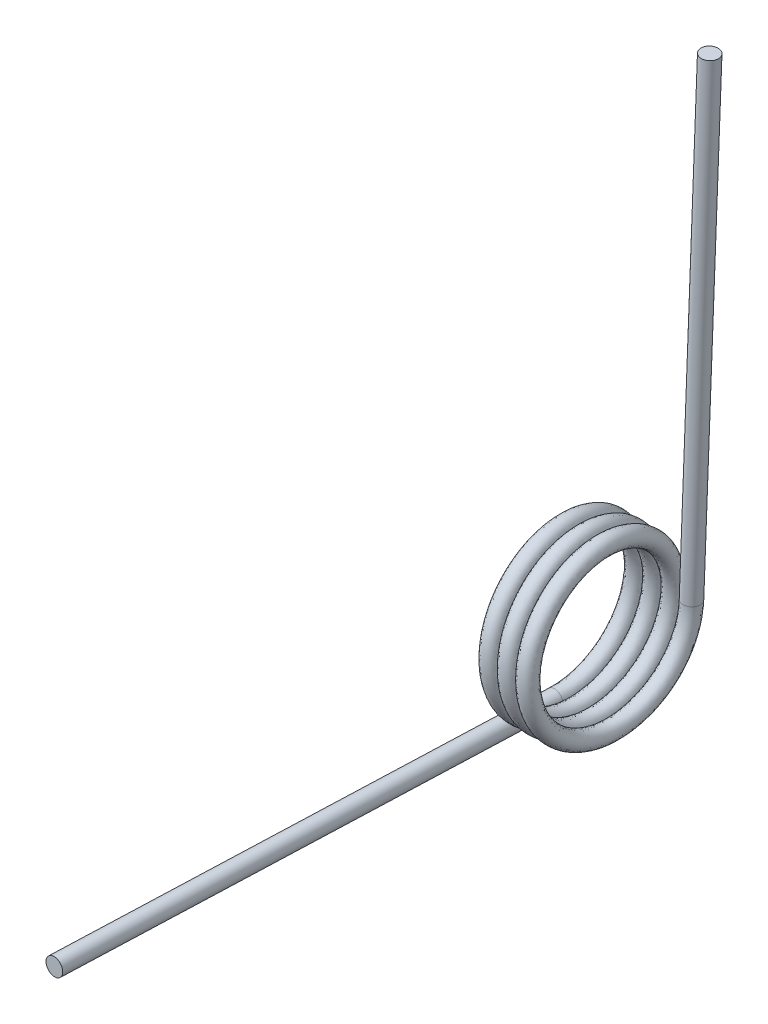
SolidWorks part; units mm, degrees
ref_plane "Front" through (0, 0, 0) normal (0, 0, 1) x (1, 0, 0)
ref_plane "Top" through (0, 0, 0) normal (0, 1, 0) x (1, 0, 0)
ref_plane "Right" through (0, 0, 0) normal (1, 0, 0) x (0, 0, -1)
sketch "Sketch1" plane through (0, 0, 0) normal (1, 0, 0) x (0, 0, -1)
  line L0 (0, 0) -> (0, -1.8034) construction
  line L1 (0, -1.8034) -> (0, -2.032) construction
  line L2 (0, -2.032) -> (0, -2.2606) construction
  circle A0 centre (0, 0) radius 1.8034 construction
  circle A1 centre (0, 0) radius 2.2606 construction
  circle A2 centre (0, 0) radius 2.032
  circle A3 centre (0, -2.032) radius 0.2286 construction
  circle A4 centre (0, 0) radius 1.3843 construction
curve "Helix/Spiral1" pitch 0.4826 height 1.5684 turns 3.25
ref_plane "Plane1" through (0, -2.032, 0) normal (0.0378, 0, -0.9993) x (0.9953, 0.0893, 0.0376)
sketch "Sketch2" plane through (0, -2.032, 0) normal (0.0378, 0, -0.9993) x (0.9953, 0.0893, 0.0376)
  circle A0 centre (0, 0) radius 0.2286
  dimension "D1" = 0.4572
sweep "Sweep1" add profiles "Sketch2" path "Helix/Spiral1"
sketch "Sketch3" plane through (0, 0, 0) normal (-0.0378, 0, 0.9993) x (-0.9953, -0.0893, -0.0376)
  circle A1 centre (0.1814, 2.0239) radius 0.2286
  circle A2 centre (0.1814, 2.0239) radius 0.2286
  dimension "D1" = 0
extrude "Extrude1" add sketch "Sketch3" along normal blind 12.7
sketch "Sketch4" plane through (0.0022, 0.0592, 0) normal (0.0378, 0.9993, 0) x (0.9953, -0.0376, -0.0893)
  circle A1 centre (1.7425, 1.884) radius 0.2286
  circle A2 centre (1.7425, 1.884) radius 0.2286
  dimension "D1" = 0
extrude "Extrude2" add sketch "Sketch4" along normal blind 12.7
sketch "Sketch5" plane through (0, 0, 0) normal (1, 0, 0) x (0, 0, -1)
  circle A0 centre (0, 0) radius 1.3843 construction
  circle A1 centre (0, 0) radius 1.3843
equation "\"D4@Helix/Spiral1\"=\"Wire Dia@Sketch1\"+.001"
equation "\"D1@Sketch2\"=\"Wire Dia@Sketch1\""
equation "\"D1@Extrude2\"=\"Leg Length@Extrude1\""
